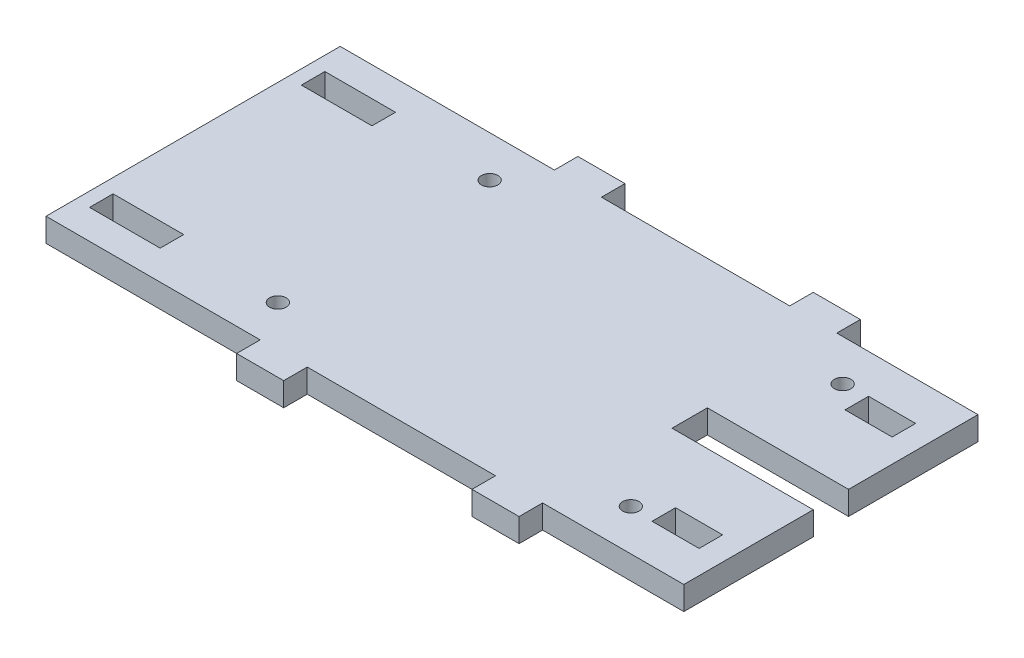
SolidWorks part; units mm, degrees
ref_plane "Front Plane" through (0, 0, 0) normal (0, 0, 1) x (1, 0, 0)
ref_plane "Top Plane" through (0, 0, 0) normal (0, 1, 0) x (1, 0, 0)
ref_plane "Right Plane" through (0, 0, 0) normal (1, 0, 0) x (0, 0, -1)
sketch "Sketch1" plane through (0, 0, 0) normal (0, 1, 0) x (1, 0, 0)
  line L8 (3.6472, 31.3591) -> (3.6472, 36.3591)
  line L9 (3.6472, 36.3591) -> (13.6472, 36.3591)
  line L10 (13.6472, 31.3591) -> (13.6472, 36.3591)
  line L16 (3.6472, -31.1409) -> (3.6472, -36.1409)
  line L17 (3.6472, -36.1409) -> (13.6472, -36.1409)
  line L18 (13.6472, -31.1409) -> (13.6472, -36.1409)
  line L45 (13.6472, 31.3591) -> (53.6472, 31.3591)
  line L46 (13.6472, -31.1409) -> (53.6472, -31.1409)
  line L47 (78.6472, -17.8909) -> (88.6472, -17.8909)
  line L49 (63.6472, -36.1409) -> (53.6472, -36.1409)
  line L50 (53.6472, -31.1409) -> (53.6472, -36.1409)
  line L52 (63.6472, 31.3591) -> (63.6472, 36.3591)
  line L53 (63.6472, 36.3591) -> (53.6472, 36.3591)
  line L54 (53.6472, 31.3591) -> (53.6472, 36.3591)
  line L56 (-23.8528, 0) -> (-23.8528, 50000) construction
  line L80 (-41.8528, 31.3591) -> (-41.8528, -31.1409)
  line L85 (93.6472, 31.3591) -> (93.6472, 3.8591)
  line L89 (88.6472, -22.8909) -> (88.6472, -17.8909)
  line L90 (63.6472, -36.1409) -> (63.6472, -31.1409)
  line L91 (93.6472, 3.8591) -> (63.6472, 3.8591)
  line L93 (93.6472, -3.6409) -> (63.6472, -3.6409)
  line L94 (63.6472, 3.8591) -> (63.6472, -3.6409)
  line L95 (63.6472, -31.1409) -> (93.6472, -31.1409)
  line L97 (93.6472, 31.3591) -> (93.6472, 3.8591)
  line L98 (93.6472, -3.6409) -> (93.6472, -31.1409)
  line L99 (26.7104, 0.1091) -> (169.6276, 0.1091) construction
  line L109 (-41.8528, 31.3591) -> (3.6472, 31.3591)
  line L110 (-41.8528, -31.1409) -> (3.6472, -31.1409)
  line L111 (-23.8528, -19.8909) -> (-38.8528, -19.8909)
  line L112 (-23.8528, 25.1091) -> (-38.8528, 25.1091)
  line L113 (-23.8528, 25.1091) -> (-23.8528, 20.1091)
  line L114 (-23.8528, 20.1091) -> (-38.8528, 20.1091)
  line L115 (-38.8528, 25.1091) -> (-38.8528, 20.1091)
  line L116 (-38.8528, -24.8909) -> (-38.8528, -19.8909)
  line L117 (-23.8528, -24.8909) -> (-38.8528, -24.8909)
  line L118 (-23.8528, -24.8909) -> (-23.8528, -19.8909)
  line L120 (63.6472, 31.3591) -> (93.6472, 31.3591)
  line L122 (-38.8528, 20.1091) -> (-38.8528, 21.8807)
  line L126 (-38.8528, -19.8909) -> (-38.8528, -21.6624)
  line L129 (78.6472, -22.8909) -> (88.6472, -22.8909)
  line L130 (78.6472, 23.1091) -> (88.6472, 23.1091)
  line L131 (78.6472, 23.1091) -> (78.6472, 18.1091)
  line L132 (78.6472, 18.1091) -> (88.6472, 18.1091)
  line L133 (88.6472, 23.1091) -> (88.6472, 18.1091)
  line L134 (78.6472, -22.8909) -> (78.6472, -17.8909)
  circle A5 centre (73.6472, 22.6091) radius 1.75
  circle A6 centre (-1.3528, 22.6091) radius 1.75
  circle A7 centre (73.6472, -22.3909) radius 1.75
  circle A8 centre (-1.3528, -22.3909) radius 1.75
  point P0 (0, 0)
  point P27 (93.1972, 30)
  point P56 (-78.3528, 1.4682)
  dimension "D28" = 0
  dimension "D29" = 0
  dimension "D31" = 31.25
  dimension "D33" = 3.75
  dimension "D34" = 3.75
  dimension "D16" = 3.5
  dimension "D17" = 3.5
  dimension "D23" = 62.5
  dimension "D24" = 31.25
  dimension "D25" = 30
  dimension "D3" = 10
  dimension "D4" = 10
  dimension "D5" = 8.75
  dimension "D6" = 10
  dimension "D7" = 5
  dimension "D8" = 5
  dimension "D9" = 18
  dimension "D10" = 5
  dimension "D11" = 5
  dimension "D12" = 10
  dimension "D13" = 22.5
  dimension "D14" = 36.5
  dimension "D15" = 75
  dimension "D18" = 10
  dimension "D19" = 15
  dimension "D20" = 5
  dimension "D21" = 30
  dimension "D22" = 20
  dimension "D26" = 0
  dimension "D27" = 40
  dimension "D30" = 30
  dimension "D32" = 31.25
  dimension "D35" = 31.25
extrude "Boss-Extrude1" add sketch "Sketch1" along normal blind 5
sketch "Sketch3" plane through (0, 0, 0) normal (0, -1, 0) x (1, 0, 0)
  circle A0 centre (-1.3528, 22.3909) radius 3.175
  circle A1 centre (73.6472, 22.3909) radius 3.175
  circle A2 centre (-1.3528, -22.6091) radius 3.175
  circle A3 centre (73.6472, -22.6091) radius 3.175
extrude "Cut-Extrude1" cut sketch "Sketch3" against normal blind 2
